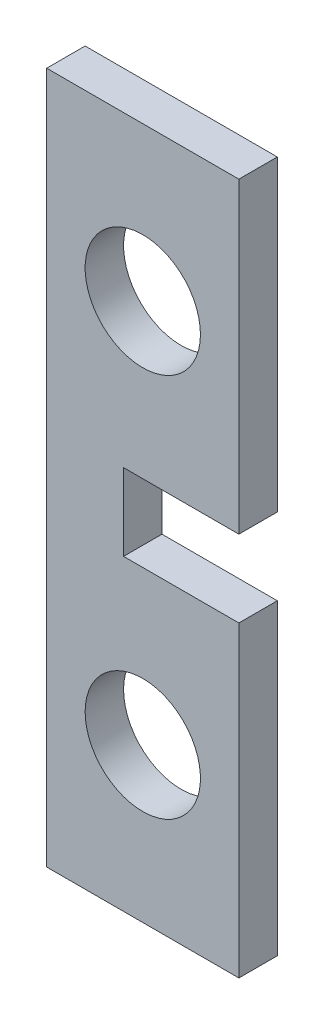
SolidWorks part; units mm, degrees
ref_plane "Front Plane" through (0, 0, 0) normal (0, 0, 1) x (1, 0, 0)
ref_plane "Top Plane" through (0, 0, 0) normal (0, 1, 0) x (1, 0, 0)
ref_plane "Right Plane" through (0, 0, 0) normal (1, 0, 0) x (0, 0, -1)
sketch "Sketch1" plane through (0, 0, 0) normal (0, 0, 1) x (1, 0, 0)
  line L1 (-2.5, -9) -> (2.5, -9)
  line L2 (-2.5, -9) -> (-2.5, 9)
  line L3 (-2.5, 9) -> (2.5, 9)
  line L4 (2.5, -9) -> (2.5, 9)
  line L5 (-2.5, -9) -> (2.5, 9) construction
  line L6 (-2.5, 9) -> (2.5, -9) construction
  point P0 (0, 0)
  dimension "D1" = 18
  dimension "D2" = 5
extrude "Boss-Extrude1" add sketch "Sketch1" along normal blind 1
sketch "Sketch2" plane through (0, 0, 1) normal (0, 0, 1) x (1, 0, 0)
  line L0 (0, 0) -> (4.6658, 0) construction
  line L1 (2.5, -9) -> (2.5, 9) construction
  line L2 (2.5, 1) -> (-0.5, 1)
  line L3 (2.5, 1) -> (2.5, -1)
  line L4 (2.5, -1) -> (-0.5, -1)
  line L5 (-0.5, 1) -> (-0.5, -1)
  circle A0 centre (0, 5) radius 1.5
  circle A1 centre (0, -5) radius 1.5
  dimension "D2" = 3
  dimension "D1" = 10
  dimension "D3" = 2
  dimension "D4" = 3
extrude "Cut-Extrude1" cut sketch "Sketch2" against normal through all
